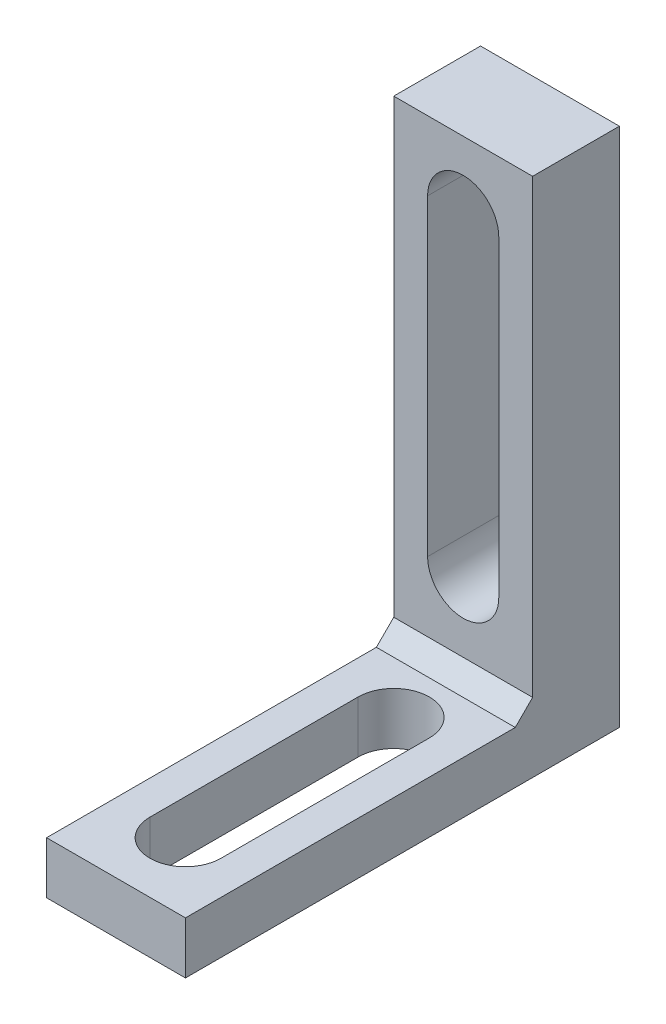
SolidWorks part; units mm, degrees
ref_plane "Front Plane" through (0, 0, 0) normal (0, 0, 1) x (1, 0, 0)
ref_plane "Top Plane" through (0, 0, 0) normal (0, 1, 0) x (1, 0, 0)
ref_plane "Right Plane" through (0, 0, 0) normal (1, 0, 0) x (0, 0, -1)
sketch "Sketch1" plane through (0, 0, 0) normal (1, 0, 0) x (0, 0, -1)
  line L0 (0, 0) -> (25, 0)
  line L1 (25, 0) -> (25, 30)
  line L2 (25, 30) -> (20, 30)
  line L3 (20, 30) -> (20, 3)
  line L4 (20, 3) -> (0, 3)
  line L5 (0, 3) -> (0, 0)
  dimension "D1" = 3
  dimension "D2" = 5
  dimension "D3" = 30
  dimension "D4" = 25
extrude "Boss-Extrude1" add sketch "Sketch1" along normal blind 8
sketch "Sketch3" plane through (0, 3, 0) normal (0, 1, 0) x (1, 0, 0)
  line L0 (4, 4) -> (4, 16) construction
  line L1 (1.95, 4) -> (1.95, 16)
  line L2 (6.05, 4) -> (6.05, 16)
  line L3 (8, 0) -> (0, 0) construction
  arc A0 (1.95, 4) -> (6.05, 4) centre (4, 4) ccw
  arc A1 (6.05, 16) -> (1.95, 16) centre (4, 16) ccw
  point P2 (4, 10)
  point P9 (4, 0)
  dimension "D2" = 4
  dimension "D1" = 12
  dimension "D3" = 4.1
extrude "Cut-Extrude1" cut sketch "Sketch3" against normal blind 8
sketch "Sketch4" plane through (0, 0, -20) normal (0, 0, 1) x (1, 0, 0)
  line L0 (4, 26) -> (4, 8) construction
  line L1 (6.05, 26) -> (6.05, 8)
  line L2 (1.95, 26) -> (1.95, 8)
  line L3 (8, 30) -> (0, 30) construction
  arc A0 (6.05, 26) -> (1.95, 26) centre (4, 26) ccw
  arc A1 (1.95, 8) -> (6.05, 8) centre (4, 8) ccw
  point P2 (4, 17)
  point P9 (4, 30)
  dimension "D1" = 4
  dimension "D2" = 4.1
  dimension "D3" = 18
extrude "Cut-Extrude2" cut sketch "Sketch4" against normal blind 8
chamfer "Chamfer1" distance 1 angle 45 1 edges at (4, 3, -20)
